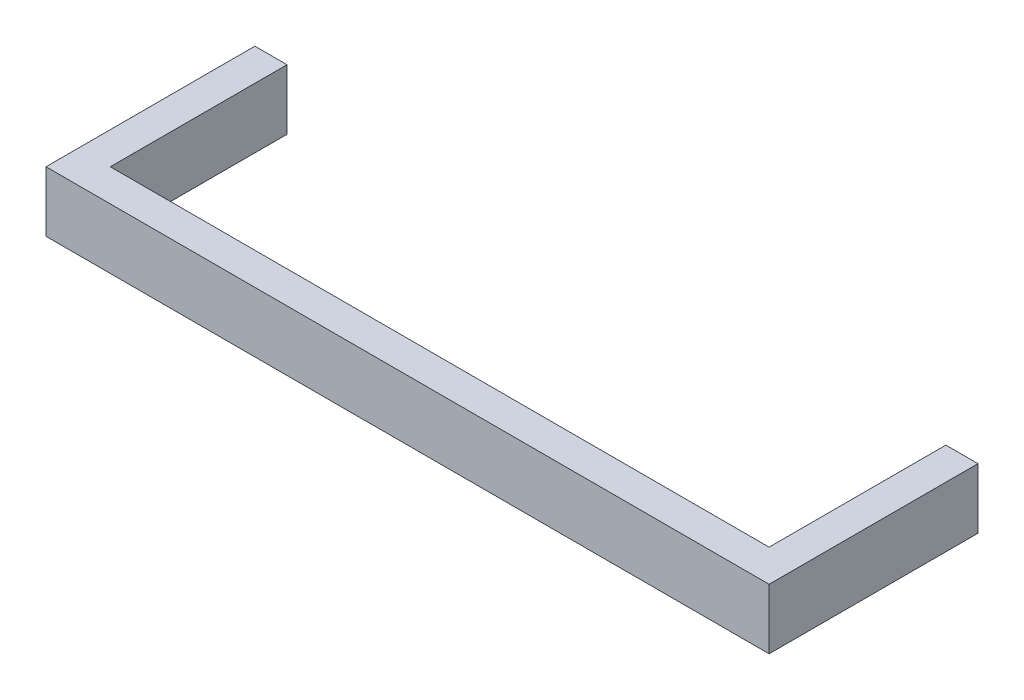
SolidWorks part; units mm, degrees
ref_plane "Front Plane" through (0, 0, 0) normal (0, 0, 1) x (1, 0, 0)
ref_plane "Top Plane" through (0, 0, 0) normal (0, 1, 0) x (1, 0, 0)
ref_plane "Right Plane" through (0, 0, 0) normal (1, 0, 0) x (0, 0, -1)
sketch "Sketch1" plane through (0, 0, 0) normal (0, 1, 0) x (1, 0, 0)
  line L0 (-16.5887, 39.0194) -> (-16.5887, 28.0194)
  line L2 (-18.5887, 39.0194) -> (-18.5887, 26.0194)
  line L3 (-18.5887, 26.0194) -> (26.4113, 26.0194)
  line L4 (26.4113, 39.0194) -> (26.4113, 26.0194)
  line L7 (-16.5887, 28.0194) -> (24.4113, 28.0194)
  line L8 (24.4113, 39.0194) -> (24.4113, 28.0194)
  line L10 (24.4113, 39.0194) -> (26.4113, 39.0194)
  line L11 (-16.5887, 39.0194) -> (-18.5887, 39.0194)
  line L12 (-18.5887, 41.0194) -> (-18.5887, 26.0194) construction
  line L13 (-18.5887, 41.0194) -> (26.4113, 41.0194) construction
  line L14 (26.4113, 41.0194) -> (26.4113, 26.0194) construction
  line L16 (-16.5887, 39.0194) -> (24.4113, 39.0194) construction
  point P0 (3.9113, 33.5194)
  dimension "D1" = 2
extrude "Boss-Extrude1" add sketch "Sketch1" along normal blind 3.75
